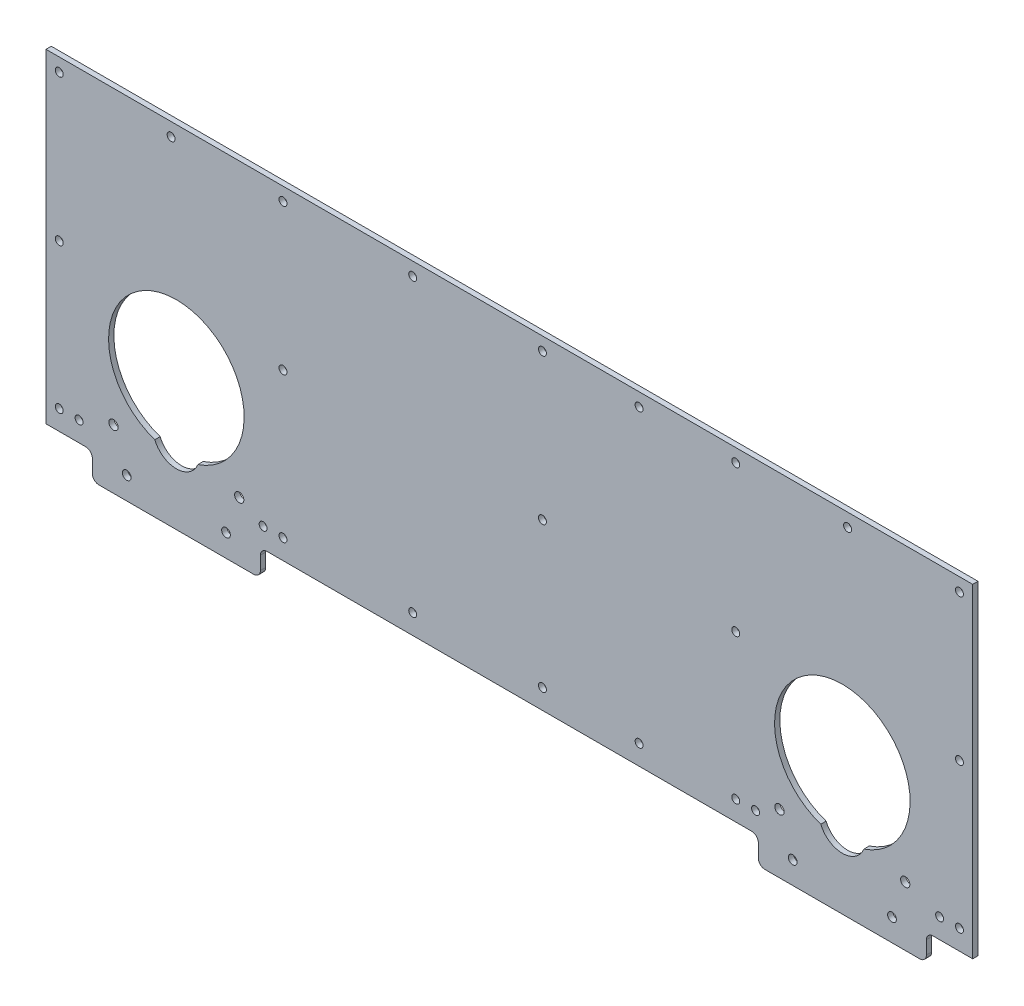
SolidWorks part; units mm, degrees
material "1345 Alloy"
ref_plane "Front Plane" through (0, 0, 0) normal (0, 0, 1) x (1, 0, 0)
ref_plane "Top Plane" through (0, 0, 0) normal (0, 1, 0) x (1, 0, 0)
ref_plane "Right Plane" through (0, 0, 0) normal (1, 0, 0) x (0, 0, -1)
sketch "Sketch1" plane through (0, 0, 0) normal (0, 0, 1) x (1, 0, 0)
  line L1 (-350, 122.5) -> (350, 122.5)
  line L2 (-350, 122.5) -> (-350, -122.5)
  line L4 (350, 122.5) -> (350, -122.5)
  line L5 (-350, 122.5) -> (350, -122.5) construction
  line L6 (-350, -122.5) -> (350, 122.5) construction
  line L9 (-350, -122.5) -> (-320, -122.5)
  line L10 (-315, -127.5) -> (-315, -137.5)
  line L11 (350, -122.5) -> (320, -122.5)
  line L12 (315, -127.5) -> (315, -137.5)
  line L13 (-188.06, -127.5) -> (-188.06, -137.5)
  line L15 (-183.06, -122.5) -> (183.06, -122.5)
  line L16 (188.06, -127.5) -> (188.06, -137.5)
  line L17 (193.06, -142.5) -> (310, -142.5)
  line L18 (-310, -142.5) -> (-193.06, -142.5)
  line L20 (-289.0304, -142.5) -> (-310, -142.5) construction
  arc A0 (320, -122.5) -> (315, -127.5) centre (320, -127.5) ccw
  arc A1 (310, -142.5) -> (315, -137.5) centre (310, -137.5) ccw
  arc A2 (-310, -142.5) -> (-315, -137.5) centre (-310, -137.5) cw
  arc A3 (-315, -127.5) -> (-320, -122.5) centre (-320, -127.5) ccw
  arc A4 (193.06, -142.5) -> (188.06, -137.5) centre (193.06, -137.5) cw
  arc A5 (188.06, -127.5) -> (183.06, -122.5) centre (183.06, -127.5) ccw
  arc A6 (-183.06, -122.5) -> (-188.06, -127.5) centre (-183.06, -127.5) ccw
  arc A7 (-188.06, -137.5) -> (-193.06, -142.5) centre (-193.06, -137.5) cw
  point P0 (0, 0)
  point P12 (315, -122.5)
  point P17 (-315, -142.5)
  point P20 (-315, -122.5)
  dimension "D6" = 5
  dimension "D7" = 5
  dimension "D1" = 700
  dimension "D2" = 245
  dimension "D3" = 35
  dimension "D4" = 35
  dimension "D5" = 20
  dimension "D8" = 126.94
  dimension "D9" = 126.94
extrude "Boss-Extrude1" add sketch "Sketch1" along normal blind 4
sketch "Sketch2" plane through (0, 0, 4) normal (0, 0, 1) x (1, 0, 0)
  line L4 (191.5296, -122.0468) -> (191.5296, -97.6368) construction
  line L5 (191.5296, -97.6368) -> (204.0296, -97.6368) construction
  line L6 (-251.5296, -43.2268) -> (-350, -43.2268) construction
  line L7 (-350, 122.5) -> (-350, -122.5) construction
  line L8 (-311.5296, -122.0468) -> (-311.5296, -97.6368) construction
  line L9 (-311.5296, -97.6368) -> (-299.0296, -97.6368) construction
  line L10 (350, -43.2268) -> (251.5296, -43.2268) construction
  line L11 (350, -122.5) -> (350, 122.5) construction
  line L12 (-214.0304, -125.6368) -> (-289.0304, -125.6368) construction
  arc A2 (-235.2738, -91.7776) -> (-267.7855, -91.7776) centre (-251.5296, -43.2268) ccw
  circle A3 centre (-299.0296, -97.6368) radius 3.5
  circle A4 centre (-204.0296, -97.6368) radius 3.5
  arc A5 (-267.7855, -91.7776) -> (-235.2738, -91.7776) centre (-251.5296, -85.1368) ccw
  circle A10 centre (-289.0304, -125.6368) radius 3.302
  circle A11 centre (-214.0304, -125.6368) radius 3.302
  arc A12 (267.7855, -91.7776) -> (235.2738, -91.7776) centre (251.5296, -43.2268) ccw
  circle A13 centre (204.0296, -97.6368) radius 3.5
  circle A14 centre (299.0296, -97.6368) radius 3.5
  arc A15 (235.2738, -91.7776) -> (267.7855, -91.7776) centre (251.5296, -85.1368) ccw
  circle A16 centre (214.0289, -125.6368) radius 3.302
  circle A17 centre (289.0289, -125.6368) radius 3.302
  point P0 (-251.5296, -85.6332)
  point P2 (251.5296, -85.6332)
  point P3 (-52.1358, -9.8326)
  dimension "D4" = 102.4
  dimension "D5" = 7
  dimension "D6" = 7
  dimension "D10" = 35.12
  dimension "D3" = 102.4
  dimension "D13" = 7
  dimension "D14" = 54.41
  dimension "D18" = 12.5
  dimension "D11" = 7
  dimension "D17" = 35.12
  dimension "D2" = 24.41
  dimension "D7" = 54.41
  dimension "D8" = 95
  dimension "D9" = 47.5
  dimension "D12" = 12.5
  dimension "D15" = 95
  dimension "D16" = 47.5
  dimension "D19" = 24.41
  dimension "D20" = 98.4704
  dimension "D21" = 98.4704
extrude "Cut-Extrude1" cut sketch "Sketch2" against normal through all
sketch "Sketch5" plane through (0, 0, 4) normal (0, 0, 1) x (1, 0, 0)
  line L0 (-340, 112.5) -> (-171, 112.5) construction
  line L1 (-325, -107.5) -> (-186, -107.5) construction
  line L2 (171, -107.5) -> (186, -107.5) construction
  line L3 (186, -107.5) -> (325, -107.5) construction
  line L4 (320, -122.5) -> (350, -122.5) construction
  line L5 (-350, -122.5) -> (-320, -122.5) construction
  line L6 (-340, -122.5) -> (-340, -107.5) construction
  line L7 (-350, 122.5) -> (-340, 122.5) construction
  line L8 (350, 122.5) -> (-350, 122.5) construction
  line L9 (-340, 122.5) -> (-340, 112.5) construction
  line L10 (25, 112.5) -> (171, 112.5) construction
  line L11 (-183.06, -122.5) -> (183.06, -122.5) construction
  line L13 (340, 112.5) -> (171, 112.5) construction
  line L14 (25, -107.5) -> (171, -107.5) construction
  line L15 (-340, 2.25) -> (340, 2.25) construction
  line L16 (-171, 112.5) -> (25, 112.5) construction
  line L17 (-171, -107.5) -> (25, -107.5) construction
  line L18 (-340, -107.5) -> (-325, -107.5) construction
  line L21 (-171, -107.5) -> (-186, -107.5) construction
  line L22 (171, -121.5) -> (171, -107.5) construction
  line L24 (-73, 112.5) -> (-73, 122.5) construction
  circle A0 centre (-340, -107.5) radius 3
  circle A1 centre (-340, 112.5) radius 3
  circle A22 centre (-171, 112.5) radius 3
  circle A23 centre (-171, -107.5) radius 3
  circle A24 centre (171, -107.5) radius 3
  circle A26 centre (340, 112.5) radius 3
  circle A27 centre (340, -107.5) radius 3
  circle A28 centre (171, 112.5) radius 3
  circle A31 centre (25, 112.5) radius 3
  circle A32 centre (25, -107.5) radius 3
  circle A33 centre (-255.5, 112.5) radius 3
  circle A34 centre (98, 112.5) radius 3
  circle A35 centre (255.5, 112.5) radius 3
  circle A36 centre (340, 2.25) radius 3
  circle A37 centre (171, 2) radius 3
  circle A38 centre (25, 2.25) radius 3
  circle A39 centre (-171, 2.25) radius 3
  circle A40 centre (-340, 2.25) radius 3
  circle A41 centre (-73, 112.5) radius 3
  circle A42 centre (-73, -107.5) radius 3
  circle A43 centre (-325, -107.5) radius 3
  circle A44 centre (186, -107.5) radius 3
  circle A45 centre (325, -107.5) radius 3
  circle A46 centre (-186, -107.5) radius 3
  circle A47 centre (98, -107.5) radius 3
  dimension "D3" = 6
  dimension "D6" = 6
  dimension "D8" = 6
  dimension "D9" = 6
  dimension "D10" = 6
  dimension "D11" = 6
  dimension "D13" = 6
  dimension "D15" = 6
  dimension "D17" = 6
  dimension "D18" = 6
  dimension "D12" = 6
  dimension "D20" = 6
  dimension "D21" = 6
  dimension "D22" = 6
  dimension "D23" = 6
  dimension "D24" = 6
  dimension "D25" = 6
  dimension "D26" = 6
  dimension "D28" = 6
  dimension "D29" = 6
  dimension "D2" = 169
  dimension "D4" = 10
  dimension "D5" = 10
  dimension "D7" = 169
  dimension "D14" = 169
  dimension "D16" = 169
  dimension "D19" = 146
  dimension "D27" = 15
  dimension "D30" = 98
  dimension "D31" = 98
  dimension "D32" = 15
  dimension "D33" = 15
  dimension "D34" = 139
  dimension "D35" = 139
  dimension "D36" = 15
  dimension "D37" = 15
  dimension "D38" = 15
  dimension "D39" = 15
  dimension "D40" = 15
  dimension "D41" = 15
  dimension "D42" = 15
  dimension "D43" = 15
  dimension "D44" = 15
  dimension "D45" = 15
  dimension "D46" = 10
  dimension "D47" = 10
  dimension "D48" = 10
  dimension "D49" = 10
  dimension "D50" = 10
  dimension "D51" = 10
  dimension "D52" = 10
  dimension "D53" = 10
extrude "Cut-Extrude2" cut sketch "Sketch5" against normal through all
